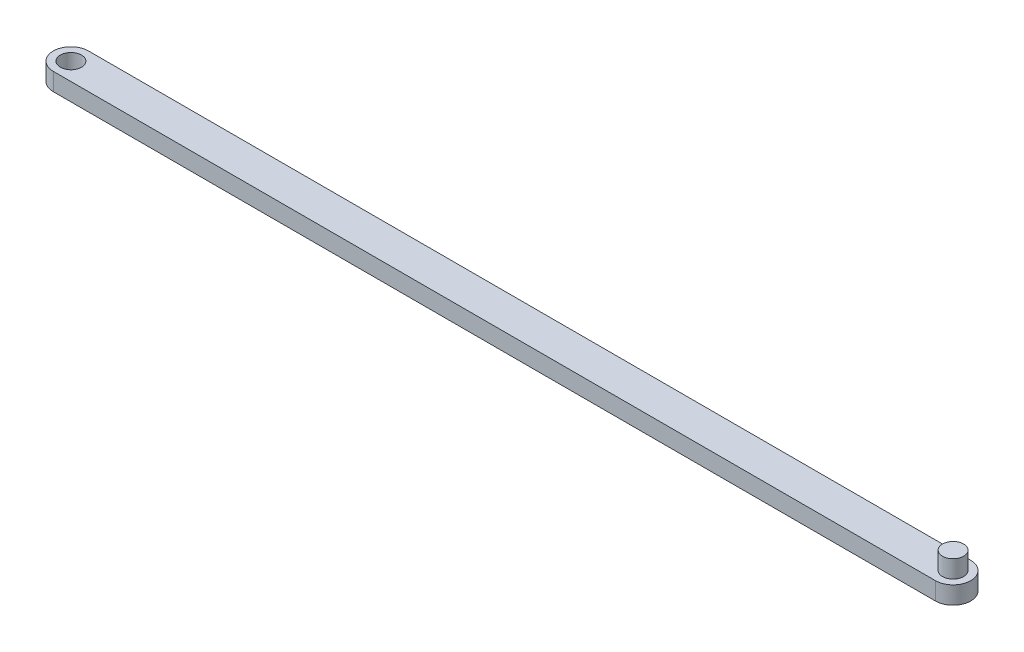
SolidWorks part; units mm, degrees
ref_plane "前视基准面" through (0, 0, 0) normal (0, 0, 1) x (1, 0, 0)
ref_plane "上视基准面" through (0, 0, 0) normal (0, 1, 0) x (1, 0, 0)
ref_plane "右视基准面" through (0, 0, 0) normal (1, 0, 0) x (0, 0, -1)
sketch "草图1" plane through (0, 0, 0) normal (0, 1, 0) x (1, 0, 0)
  line L0 (-106.6888, 0) -> (107.0504, 0) construction
  line L1 (0, 77.9371) -> (0, -83.7236) construction
  line L2 (-92.1101, 6.2176) -> (157.8899, 6.2176)
  line L4 (157.8899, -3.7824) -> (-92.1101, -3.7824)
  arc A0 (157.8899, -3.7824) -> (157.8899, 6.2176) centre (157.8899, 1.2176) ccw
  arc A1 (-92.1101, 6.2176) -> (-92.1101, -3.7824) centre (-92.1101, 1.2176) ccw
  circle A2 centre (-92.1101, 1.2176) radius 3
  dimension "D1" = 250
  dimension "D2" = 5
extrude "凸台-拉伸1" add sketch "草图1" along normal blind 5
sketch "草图2" plane through (0, 5, 0) normal (0, 1, 0) x (1, 0, 0)
  circle A0 centre (157.8899, 1.2176) radius 3
extrude "凸台-拉伸2" add sketch "草图2" along normal blind 5
